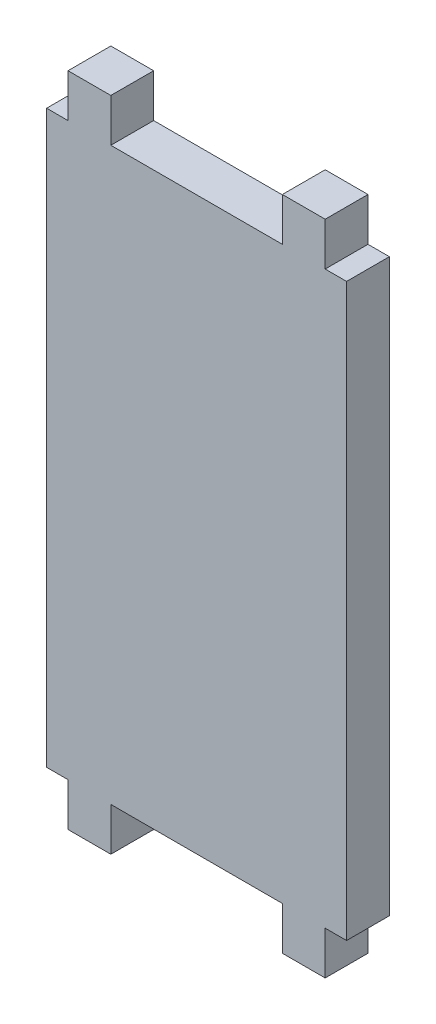
SolidWorks part; units mm, degrees
ref_plane "Alzado" through (0, 0, 0) normal (0, 0, 1) x (1, 0, 0)
ref_plane "Planta" through (0, 0, 0) normal (0, 1, 0) x (1, 0, 0)
ref_plane "Vista lateral" through (0, 0, 0) normal (1, 0, 0) x (0, 0, -1)
sketch "Model" plane through (0, 0, 0) normal (0, 0, 1) x (1, 0, 0)
  line L0 (31.9795, 103.95) -> (37.9795, 103.95)
  line L1 (71.0198, 110) -> (71.0209, 190)
  line L2 (68.0197, 103.95) -> (68.0198, 110)
  line L3 (62.0197, 103.95) -> (62.0198, 110)
  line L4 (37.9799, 196.05) -> (37.9798, 190)
  line L5 (31.9799, 196.05) -> (31.9798, 190)
  line L6 (28.9795, 190) -> (28.9795, 110)
  line L7 (28.9795, 110) -> (31.9795, 110)
  line L8 (28.9795, 190) -> (31.9798, 190)
  line L9 (31.9799, 196.05) -> (37.9799, 196.05)
  line L10 (62.021, 196.05) -> (68.021, 196.05)
  line L11 (62.0197, 103.95) -> (68.0197, 103.95)
  line L12 (37.9798, 190) -> (62.0209, 190)
  line L13 (68.0209, 190) -> (71.0209, 190)
  line L14 (62.0209, 190) -> (62.021, 196.05)
  line L15 (37.9795, 110) -> (37.9795, 103.95)
  line L16 (31.9795, 110) -> (31.9795, 103.95)
  line L17 (68.0209, 190) -> (68.021, 196.05)
  line L18 (37.9795, 110) -> (62.0198, 110)
  line L19 (68.0198, 110) -> (71.0198, 110)
extrude "Saliente-Extruir1" add sketch "Model" along normal blind 6
